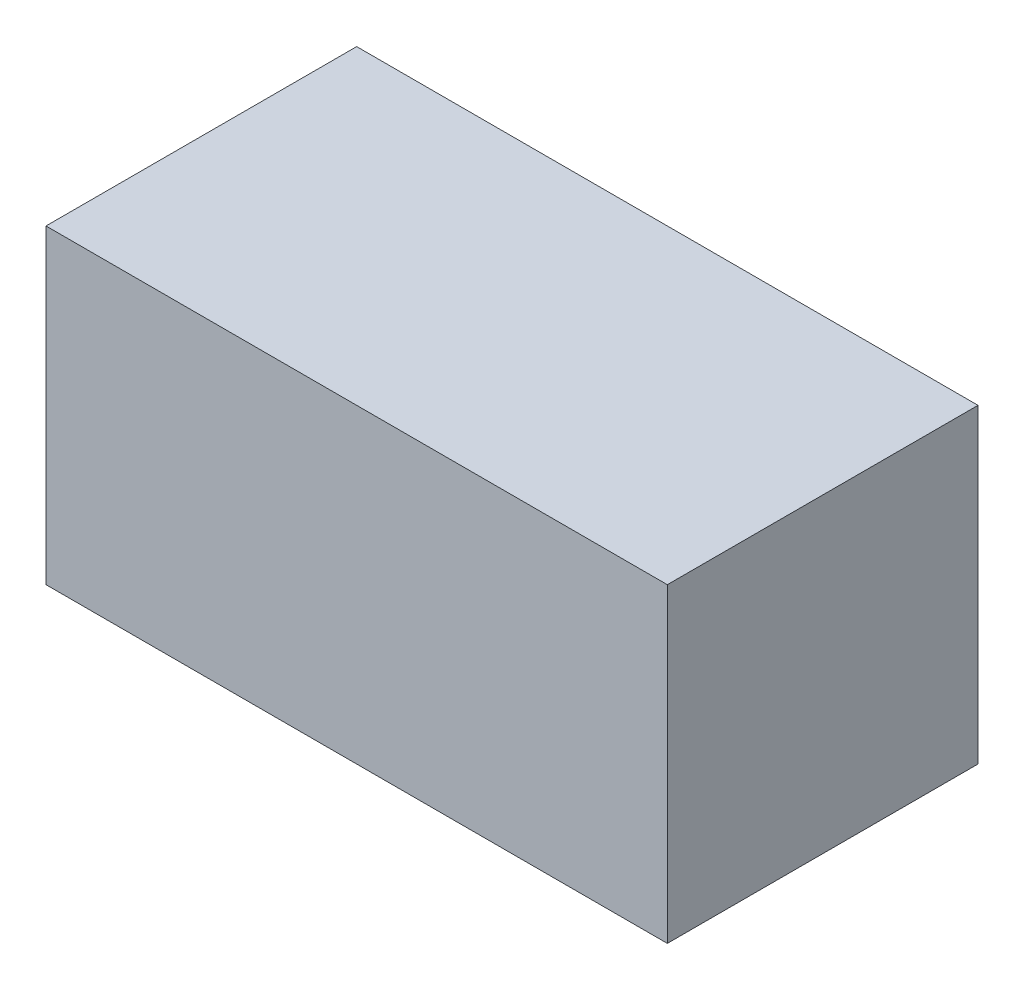
SolidWorks part; units mm, degrees
ref_plane "Front Plane" through (0, 0, 0) normal (0, 0, 1) x (1, 0, 0)
ref_plane "Top Plane" through (0, 0, 0) normal (0, 1, 0) x (1, 0, 0)
ref_plane "Right Plane" through (0, 0, 0) normal (1, 0, 0) x (0, 0, -1)
sketch "Sketch1" plane through (0, 0, 0) normal (0, 1, 0) x (1, 0, 0)
  line L1 (-20, -10) -> (20, -10)
  line L2 (-20, -10) -> (-20, 10)
  line L3 (-20, 10) -> (20, 10)
  line L4 (20, -10) -> (20, 10)
  line L5 (-20, -10) -> (20, 10) construction
  line L6 (-20, 10) -> (20, -10) construction
  point P0 (0, 0)
  dimension "D1" = 39.9999
  dimension "D2" = 20
extrude "Boss-Extrude1" add sketch "Sketch1" along normal blind 20
